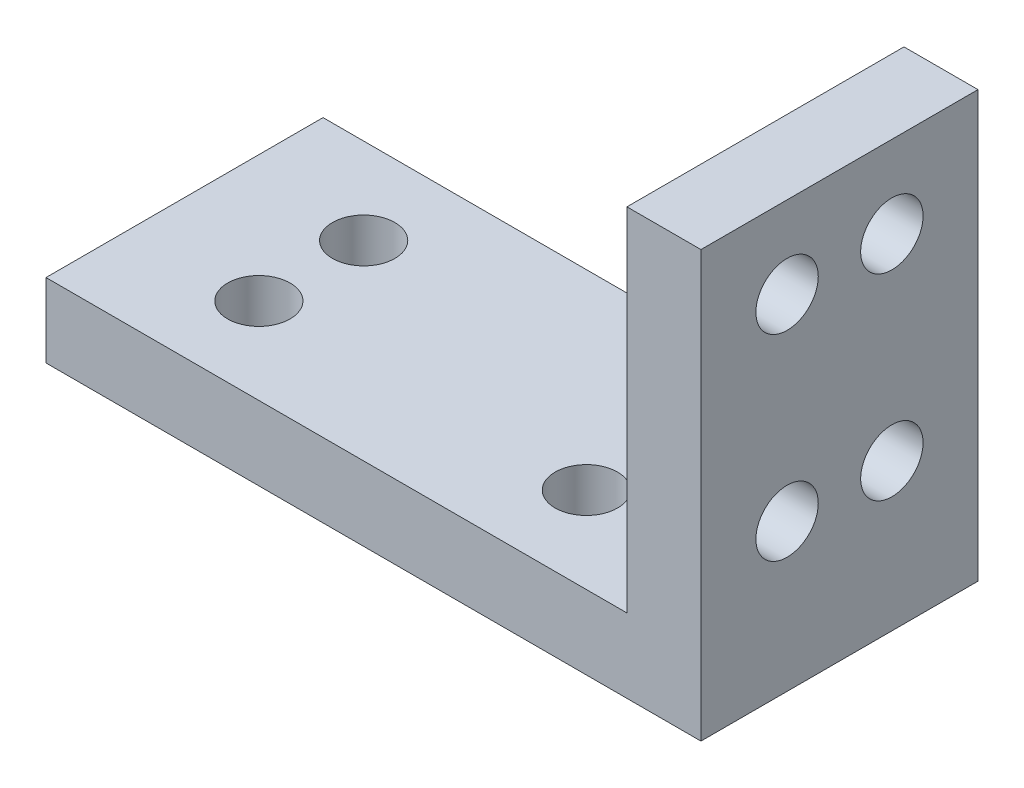
SolidWorks part; units mm, degrees
ref_plane "Front Plane" through (0, 0, 0) normal (0, 0, 1) x (1, 0, 0)
ref_plane "Top Plane" through (0, 0, 0) normal (0, 1, 0) x (1, 0, 0)
ref_plane "Right Plane" through (0, 0, 0) normal (1, 0, 0) x (0, 0, -1)
sketch "Sketch1" plane through (0, 0, 0) normal (0, 1, 0) x (1, 0, 0)
  line L1 (0, 0) -> (100, 0)
  line L2 (0, 0) -> (0, -42.3)
  line L3 (0, -42.3) -> (100, -42.3)
  line L4 (100, 0) -> (100, -42.3)
  dimension "D1" = 42.3
  dimension "D2" = 100
extrude "Boss-Extrude1" add sketch "Sketch1" along normal blind 11.3
sketch "Sketch2" plane through (0, 11.3, 0) normal (0, 1, 0) x (1, 0, 0)
  line L0 (0, -42.3) -> (100, -42.3) construction
  line L1 (100, 0) -> (88.7, 0)
  line L2 (100, 0) -> (100, -42.3)
  line L3 (100, -42.3) -> (88.7, -42.3)
  line L4 (88.7, 0) -> (88.7, -42.3)
  dimension "D1" = 11.3
extrude "Boss-Extrude2" add sketch "Sketch2" along normal blind 53.7 contours L4 L3 L2 L1
sketch "Sketch3" plane through (100, 0, 0) normal (1, 0, 0) x (0, 0, -1)
  line L0 (-42.3, 0) -> (0, 0) construction
  line L1 (0, 65) -> (0, 0) construction
  circle A0 centre (-13.15, 22.5) radius 4.7625
  circle A1 centre (-13.15, 52.5) radius 4.7625
  circle A2 centre (-29.15, 52.5) radius 4.7625
  circle A3 centre (-29.15, 22.5) radius 4.7625
  point P8 (0, 0)
  point P9 (0, 0)
  point P10 (0, 0)
  point P11 (0, 0)
  point P12 (0, 0)
  point P13 (-12.848, 30.8055)
  dimension "D1" = 9.525
  dimension "D2" = 9.525
  dimension "D3" = 9.525
  dimension "D4" = 9.525
  dimension "D5" = 16
  dimension "D6" = 22.5
  dimension "D7" = 30
  dimension "D8" = 13.15
extrude "Cut-Extrude1" cut sketch "Sketch3" against normal blind 53.7
sketch "Sketch4" plane through (0, 11.3, 0) normal (0, 1, 0) x (1, 0, 0)
  line L0 (0, -42.3) -> (88.7, -42.3) construction
  line L2 (0, 0) -> (0, -42.3) construction
  circle A0 centre (19.35, -13.15) radius 4.7625
  circle A1 centre (69.35, -13.15) radius 4.7625
  circle A2 centre (19.35, -29.15) radius 4.7625
  circle A3 centre (69.35, -29.15) radius 4.7625
  point P8 (0, 0)
  point P9 (0, 0)
  point P10 (0, 0)
  point P11 (0, 0)
  point P12 (0, 0)
  point P13 (0, 0)
  point P14 (0, 0)
  dimension "D1" = 9.525
  dimension "D2" = 9.525
  dimension "D3" = 9.525
  dimension "D4" = 9.525
  dimension "D5" = 16
  dimension "D6" = 13.15
  dimension "D7" = 50
  dimension "D8" = 19.35
extrude "Cut-Extrude2" cut sketch "Sketch4" against normal blind 53.7
